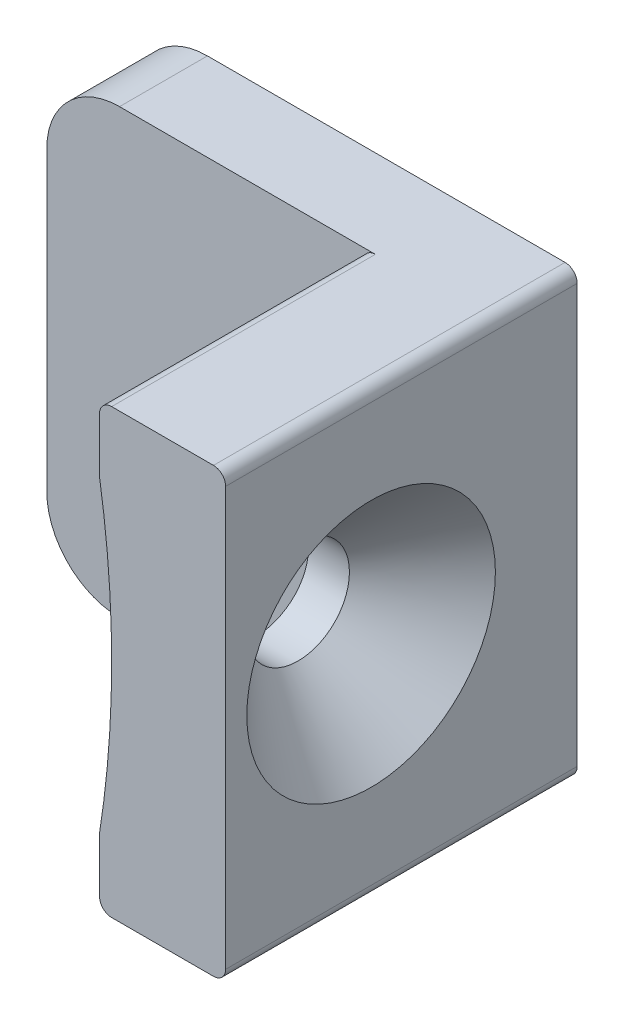
SolidWorks part; units mm, degrees
ref_plane "Front Plane" through (0, 0, 0) normal (0, 0, 1) x (1, 0, 0)
ref_plane "Top Plane" through (0, 0, 0) normal (0, 1, 0) x (1, 0, 0)
ref_plane "Right Plane" through (0, 0, 0) normal (1, 0, 0) x (0, 0, -1)
sketch "Sketch1" plane through (0, 0, 0) normal (0, 1, 0) x (1, 0, 0)
  line L0 (-18.542, 4.953) -> (-7.62, 4.953)
  line L1 (0, 8.636) -> (-18.542, 8.636)
  line L2 (0, 8.636) -> (0, -6.096)
  line L3 (0, -6.096) -> (-7.62, -6.096)
  line L4 (-18.542, 8.636) -> (-18.542, 4.953)
  line L5 (-7.62, 4.953) -> (-7.62, -6.096)
  point P4 (0, 0)
  dimension "D1" = 14.732
  dimension "D2" = 18.542
  dimension "D3" = 4.953
  dimension "D4" = 7.62
  dimension "D5" = 6.096
  dimension "D6" = 3.683
extrude "Boss-Extrude1" add sketch "Sketch1" along normal mid plane 18.542
sketch "Sketch2" plane through (0, 0, -4.953) normal (0, 0, -1) x (-1, 0, 0)
  line L0 (5.2832, 6.4618) -> (5.2832, 15.24)
  line L1 (52.0022, 15.24) -> (5.2832, 15.24)
  line L2 (52.0022, 15.24) -> (52.0022, -15.24)
  line L3 (52.0022, -15.24) -> (5.2832, -15.24)
  line L4 (-4.1097, 0) -> (-11.6822, 0) construction
  line L5 (5.2832, -6.4618) -> (5.2832, -15.24)
  arc A0 (5.2832, -6.4618) -> (5.2832, 6.4618) centre (46.1264, 0) cw
  dimension "D1" = 41.3512
  dimension "D2" = 0.508
  dimension "D4" = 4.7752
  dimension "D3" = 30.48
extrude "Cut-Extrude1" cut sketch "Sketch2" against normal through all
hole_wizard "CSK for M4 Flat Head Machine Screw1" positions "Sketch4" profile "Sketch3" countersink size "M4" standard "Ansi Metric" end condition through all
sketch "Sketch4" plane through (0, 0, 0) normal (1, 0, 0) x (0, 0, -1)
  point P0 (0, 0)
sketch "Sketch3" plane through (0, 0, 0) normal (0, 1, 0) x (0, 0, -1)
  line L0 (0, 0) -> (0, 18.542)
  line L1 (0, 18.542) -> (2.15, 18.542)
  line L2 (2.15, 18.542) -> (2.15, 3.058)
  line L3 (2.15, 3.058) -> (5.208, 0)
  line L5 (5.208, 0) -> (0, 0)
  line L6 (-2.15, 3.058) -> (-5.208, 0) construction
  line L11 (0, -6.35) -> (0, 107.95) construction
  dimension "Thru Hole Dia." = 4.3
  dimension "Thru Hole Depth" = 18.542
  dimension "Near C'Sink Dia." = 10.416
  dimension "Near C'Sink Angle" = 90
hole_wizard "#6-32 Tapped Hole1" positions "Sketch6" profile "Sketch5" tap size "#6-32" standard "Ansi Inch" end condition up to next
sketch "Sketch6" plane through (-24.7065, -9.1224, -8.636) normal (0, 0, 1) x (1, 0, 0)
  point P0 (12.0065, 5.9474)
  dimension "D1" = 3.175
  dimension "D2" = 12.7
cosmetic thread "Hole Thread2" parameters "D2"=3.5052
sketch "Sketch5" plane through (-12.7, -3.175, -8.636) normal (1, 0, 0) x (0, 1, 0)
  line L0 (0, 0) -> (0, 3.683)
  line L1 (0, 3.683) -> (1.905, 3.683)
  line L2 (1.3525, 3.1305) -> (1.3525, 0.5524)
  line L3 (1.3525, 0.5524) -> (1.905, 0)
  line L5 (1.905, 0) -> (0, 0)
  line L6 (-1.3525, 0.5524) -> (-1.905, 0) construction
  line L7 (1.905, 3.683) -> (1.3525, 3.1305)
  line L8 (-1.905, 3.683) -> (-1.3526, 3.1305) construction
  line L11 (0, -6.35) -> (0, 107.95) construction
  dimension "Thru Tap Drill Dia." = 2.7051
  dimension "Thru Tap Drill Depth" = 3.683
  dimension "Near C'Sink Dia." = 3.81
  dimension "Near C'Sink Angle" = 90
  dimension "Far C'Sink Dia." = 3.81
  dimension "Far C'Sink Angle" = 90
fillet "Fillet2" radius 3.048 2 edges at (-18.542, -9.271, -6.7945) (-18.542, 9.271, -6.7945)
fillet "Fillet3" radius 0.508 4 edges at (0, -9.271, -1.27) (0, 9.271, -1.27) (-5.2832, 9.271, 0.5715) (-5.2832, -9.271, 0.5715)
pattern_linear "LPattern1" [suppressed] count 3 spacing 25.4
